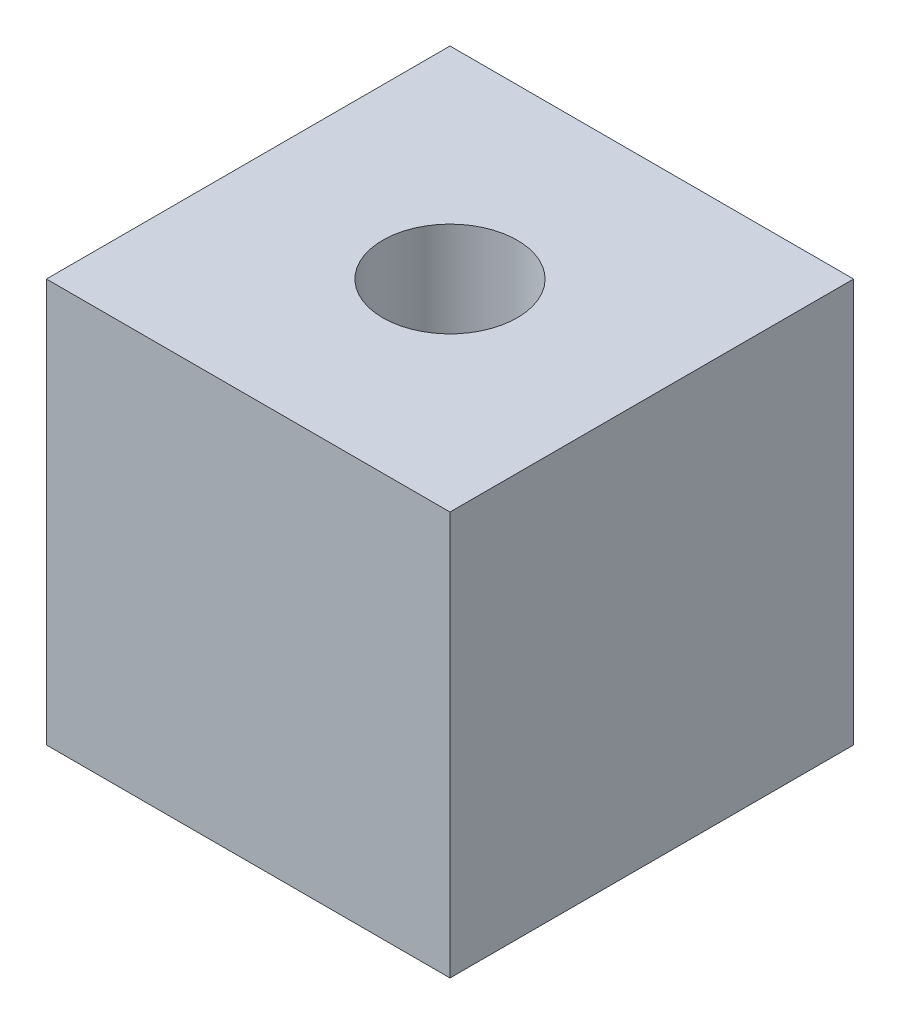
SolidWorks part; units mm, degrees
ref_plane "Front Plane" through (0, 0, 0) normal (0, 0, 1) x (1, 0, 0)
ref_plane "Top Plane" through (0, 0, 0) normal (0, 1, 0) x (1, 0, 0)
ref_plane "Right Plane" through (0, 0, 0) normal (1, 0, 0) x (0, 0, -1)
sketch "Sketch1" plane through (0, 0, 0) normal (0, 1, 0) x (1, 0, 0)
  line L1 (0, 0) -> (12, 0)
  line L2 (0, 0) -> (0, -12)
  line L3 (0, -12) -> (12, -12)
  line L4 (12, 0) -> (12, -12)
  circle A0 centre (6, -6) radius 2
  dimension "D3" = 4
  dimension "D1" = 12
  dimension "D2" = 12
  dimension "D4" = 6
  dimension "D5" = 6
extrude "Boss-Extrude1" add sketch "Sketch1" along normal blind 12
